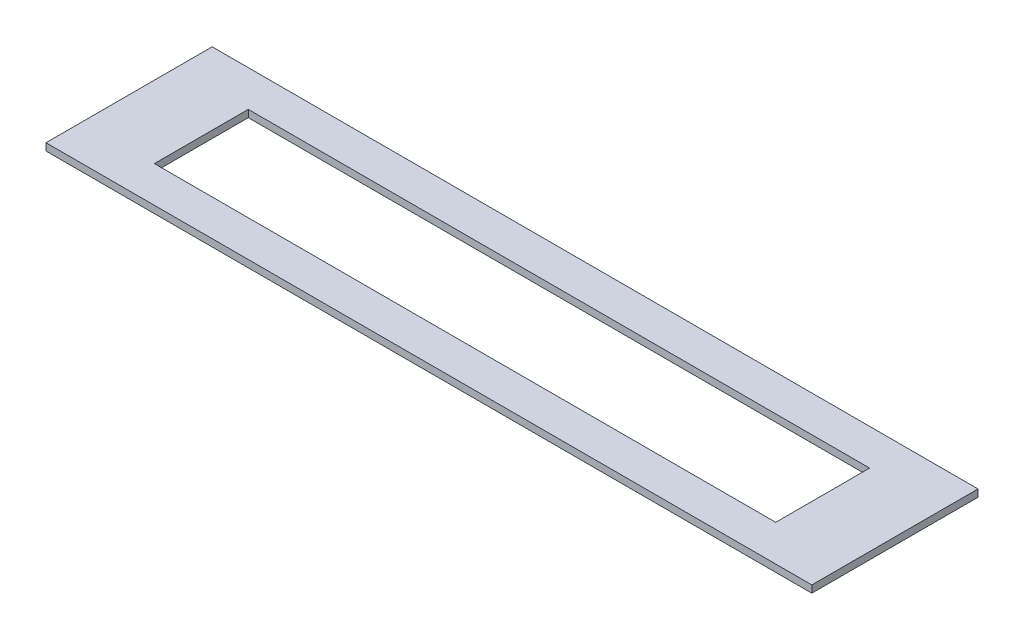
SolidWorks part; units mm, degrees
ref_plane "Front Plane" through (0, 0, 0) normal (0, 0, 1) x (1, 0, 0)
ref_plane "Top Plane" through (0, 0, 0) normal (0, 1, 0) x (1, 0, 0)
ref_plane "Right Plane" through (0, 0, 0) normal (1, 0, 0) x (0, 0, -1)
sketch "Sketch1" plane through (0, 0, 0) normal (0, 1, 0) x (1, 0, 0)
  line L1 (0, 0) -> (530, 0)
  line L2 (0, 0) -> (0, 115)
  line L3 (0, 115) -> (530, 115)
  line L4 (530, 0) -> (530, 115)
  line L5 (50, 90) -> (480, 90)
  line L6 (50, 90) -> (50, 25)
  line L7 (50, 25) -> (480, 25)
  line L8 (480, 90) -> (480, 25)
  dimension "D1" = 530
  dimension "D2" = 115
  dimension "D3" = 65
  dimension "D4" = 430
  dimension "D5" = 25
  dimension "D6" = 25
  dimension "D7" = 50
  dimension "D8" = 50
extrude "Boss-Extrude1" add sketch "Sketch1" along normal blind 5
